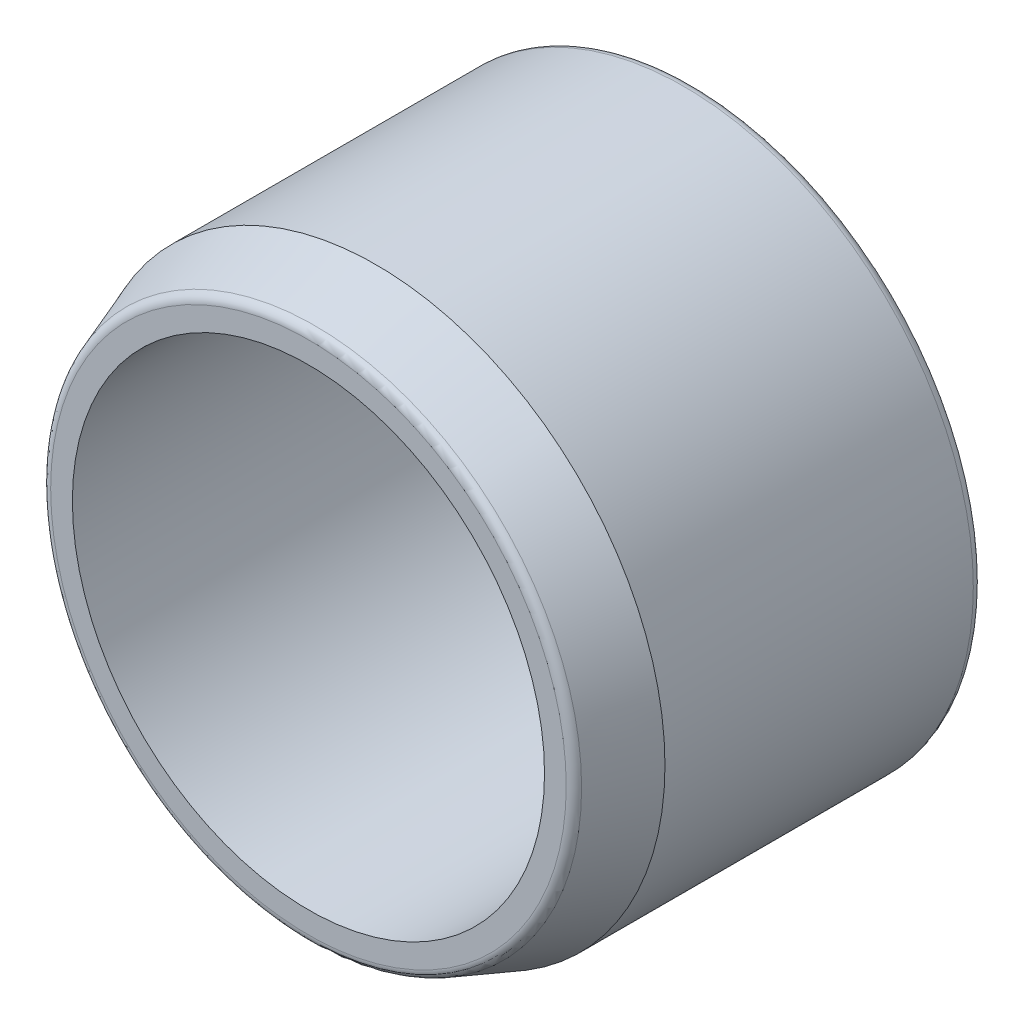
SolidWorks part; units mm, degrees
ref_plane "Płaszczyzna przednia" through (0, 0, 0) normal (0, 0, 1) x (1, 0, 0)
ref_plane "Płaszczyzna górna" through (0, 0, 0) normal (0, 1, 0) x (1, 0, 0)
ref_plane "Płaszczyzna prawa" through (0, 0, 0) normal (1, 0, 0) x (0, 0, -1)
sketch "Szkic1" plane through (0, 0, 0) normal (0, 0, 1) x (1, 0, 0)
  circle A0 centre (0, 0) radius 30
  circle A1 centre (0, 0) radius 24.5
  dimension "D1" = 60
  dimension "D2" = 49
extrude "Dodanie-wyciągnięcie1" add sketch "Szkic1" along normal blind 40
chamfer "Sfazowanie1" distance 7 angle 20 1 edges at (30, 0, 40)
fillet "Zaokrąglenie1" radius 1 2 edges at (30, 0, 0) (27.4522, 0, 40)
